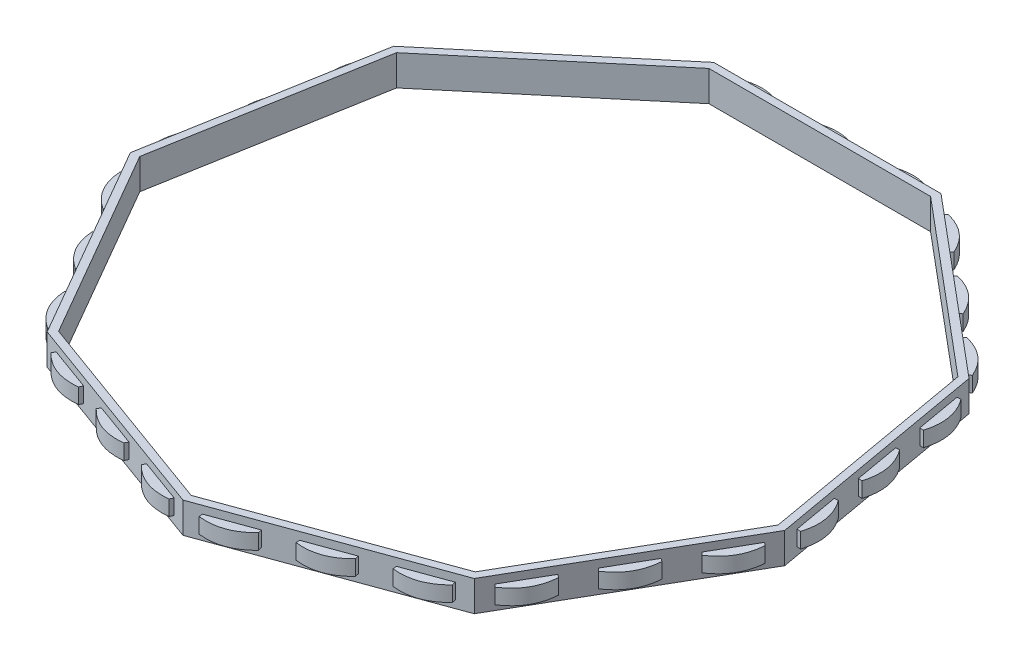
SolidWorks part; units mm, degrees
ref_plane "Front" through (0, 0, 0) normal (0, 0, 1) x (1, 0, 0)
ref_plane "Top" through (0, 0, 0) normal (0, 1, 0) x (1, 0, 0)
ref_plane "Right" through (0, 0, 0) normal (1, 0, 0) x (0, 0, -1)
sketch "Esboço1" plane through (0, 0, 0) normal (0, 1, 0) x (1, 0, 0)
  line L9 (90.0427, -15.0933) -> (79.7183, 43.4593)
  line L10 (79.7183, 43.4593) -> (34.1725, 81.6768)
  line L11 (34.1725, 81.6768) -> (-25.2834, 81.6768)
  line L12 (-25.2834, 81.6768) -> (-70.8293, 43.4593)
  line L13 (-70.8293, 43.4593) -> (-81.1537, -15.0933)
  line L14 (-81.1537, -15.0933) -> (-51.4257, -66.5836)
  line L15 (-51.4257, -66.5836) -> (4.4445, -86.9187)
  line L16 (4.4445, -86.9187) -> (60.3148, -66.5836)
  line L17 (60.3148, -66.5836) -> (90.0427, -15.0933)
  line L18 (-24.5555, 79.6768) -> (-68.986, 42.3952)
  line L19 (-68.986, 42.3952) -> (-79.0576, -14.7237)
  line L20 (-79.0576, -14.7237) -> (-50.0576, -64.9532)
  line L21 (-50.0576, -64.9532) -> (4.4445, -84.7903)
  line L22 (4.4445, -84.7903) -> (58.9467, -64.9532)
  line L23 (58.9467, -64.9532) -> (87.9467, -14.7237)
  line L24 (87.9467, -14.7237) -> (77.8751, 42.3952)
  line L25 (77.8751, 42.3952) -> (33.4445, 79.6768)
  line L26 (33.4445, 79.6768) -> (-24.5555, 79.6768)
  line L27 (-24.5555, 79.6768) -> (-68.986, 42.3952)
  line L28 (-68.986, 42.3952) -> (-79.0576, -14.7237)
  line L29 (-79.0576, -14.7237) -> (-50.0576, -64.9532)
  line L30 (-50.0576, -64.9532) -> (4.4445, -84.7903)
  line L31 (4.4445, -84.7903) -> (58.9467, -64.9532)
  line L32 (58.9467, -64.9532) -> (87.9467, -14.7237)
  line L33 (87.9467, -14.7237) -> (77.8751, 42.3952)
  line L34 (77.8751, 42.3952) -> (33.4445, 79.6768)
  line L35 (33.4445, 79.6768) -> (-24.5555, 79.6768)
  dimension "D1" = 0
  dimension "D2" = 2
extrude "Ressalto-extrusão1" add sketch "Esboço1" along normal mid plane 8
sketch "Esboço3" plane through (0, 0, 0) normal (0, 1, 0) x (1, 0, 0)
  line L0 (19.4796, -81.4464) -> (8.2033, -85.5506)
  line L1 (8.2033, -85.5506) -> (8.2988, -86.546)
  line L2 (4.4445, -86.9187) -> (60.3148, -66.5836) construction
  line L3 (19.7122, -82.4189) -> (19.4796, -81.4464)
  line L4 (38.0762, -74.6778) -> (26.7998, -78.782)
  line L5 (19.7122, -82.4189) -> (15.0322, -87.3218) construction
  line L6 (15.0322, -87.3218) -> (8.2988, -86.546) construction
  line L7 (26.7998, -78.782) -> (26.8953, -79.7775)
  line L8 (38.3088, -75.6503) -> (38.0762, -74.6778)
  line L9 (38.3088, -75.6503) -> (33.6287, -80.5532) construction
  line L10 (33.6287, -80.5532) -> (26.8953, -79.7775) construction
  line L11 (56.6727, -67.9092) -> (45.3964, -72.0134)
  line L12 (45.3964, -72.0134) -> (45.4918, -73.0089)
  line L13 (56.9053, -68.8818) -> (56.6727, -67.9092)
  line L14 (56.9053, -68.8818) -> (52.2253, -73.7846) construction
  line L15 (52.2253, -73.7846) -> (45.4918, -73.0089) construction
  line L16 (-36.3906, -72.0559) -> (-47.6669, -67.9517)
  line L17 (-47.6669, -67.9517) -> (-48.2337, -68.7756)
  line L18 (-36.8376, -72.9504) -> (-36.3906, -72.0559)
  line L19 (-17.7941, -78.8245) -> (-29.0704, -74.7202)
  line L20 (-29.0704, -74.7202) -> (-29.6371, -75.5441)
  line L21 (-18.2411, -79.719) -> (-17.7941, -78.8245)
  line L22 (0.8024, -85.5931) -> (-10.4739, -81.4888)
  line L23 (-10.4739, -81.4888) -> (-11.0406, -82.3127)
  line L24 (0.3555, -86.4876) -> (0.8024, -85.5931)
  line L25 (-36.8376, -72.9504) -> (-43.5742, -73.698) construction
  line L26 (-43.5742, -73.698) -> (-48.2337, -68.7756) construction
  line L27 (-18.2411, -79.719) -> (-24.9777, -80.4666) construction
  line L28 (-24.9777, -80.4666) -> (-29.6371, -75.5441) construction
  line L29 (0.3555, -86.4876) -> (-6.3812, -87.2352) construction
  line L31 (-6.3812, -87.2352) -> (-11.0406, -82.3127) construction
  line L32 (-73.1537, -28.9497) -> (-79.1537, -18.5574)
  line L33 (-79.1537, -18.5574) -> (-80.1174, -18.8242)
  line L34 (-74.0711, -29.3476) -> (-73.1537, -28.9497)
  line L35 (-63.2586, -46.0883) -> (-69.2586, -35.696)
  line L36 (-69.2586, -35.696) -> (-70.2224, -35.9629)
  line L37 (-64.176, -46.4863) -> (-63.2586, -46.0883)
  line L38 (-53.3636, -63.227) -> (-59.3636, -52.8347)
  line L39 (-59.3636, -52.8347) -> (-60.3274, -53.1015)
  line L40 (-54.281, -63.625) -> (-53.3636, -63.227)
  line L41 (-74.0711, -29.3476) -> (-79.7121, -25.5901) construction
  line L42 (-79.7121, -25.5901) -> (-80.1174, -18.8242) construction
  line L43 (-64.176, -46.4863) -> (-69.8171, -42.7287) construction
  line L44 (-69.8171, -42.7287) -> (-70.2224, -35.9629) construction
  line L45 (-54.281, -63.625) -> (-59.9221, -59.8674) construction
  line L46 (-59.9221, -59.8674) -> (-60.3274, -53.1015) construction
  line L47 (-73.6076, 27.7024) -> (-71.5238, 39.5201)
  line L48 (-71.5238, 39.5201) -> (-72.4336, 39.9352)
  line L49 (-74.5662, 27.9873) -> (-73.6076, 27.7024)
  line L50 (-77.0441, 8.2131) -> (-74.9603, 20.0307)
  line L51 (-74.9603, 20.0307) -> (-75.8701, 20.4458)
  line L52 (-78.0027, 8.4979) -> (-77.0441, 8.2131)
  line L53 (-80.4806, -11.2763) -> (-78.3968, 0.5414)
  line L54 (-78.3968, 0.5414) -> (-79.3066, 0.9564)
  line L55 (-81.4392, -10.9915) -> (-80.4806, -11.2763)
  line L56 (-74.5662, 27.9873) -> (-76.4722, 34.4917) construction
  line L57 (-76.4722, 34.4917) -> (-72.4336, 39.9352) construction
  line L58 (-78.0027, 8.4979) -> (-79.9087, 15.0024) construction
  line L59 (-79.9087, 15.0024) -> (-75.8701, 20.4458) construction
  line L60 (-81.4392, -10.9915) -> (-83.3452, -4.487) construction
  line L63 (-83.3452, -4.487) -> (-79.3066, 0.9564) construction
  line L64 (-37.5401, 71.3922) -> (-28.3476, 79.1057)
  line L65 (-28.3476, 79.1057) -> (-28.7777, 80.0085)
  line L66 (-38.0913, 72.2266) -> (-37.5401, 71.3922)
  line L67 (-52.7001, 58.6715) -> (-43.5076, 66.3849)
  line L68 (-43.5076, 66.3849) -> (-43.9378, 67.2877)
  line L69 (-53.2514, 59.5058) -> (-52.7001, 58.6715)
  line L70 (-67.8602, 45.9507) -> (-58.6676, 53.6641)
  line L71 (-58.6676, 53.6641) -> (-59.0978, 54.5669)
  line L72 (-68.4114, 46.785) -> (-67.8602, 45.9507)
  line L73 (-38.0913, 72.2266) -> (-35.3704, 78.4345) construction
  line L74 (-35.3704, 78.4345) -> (-28.7777, 80.0085) construction
  line L75 (-53.2514, 59.5058) -> (-50.5305, 65.7137) construction
  line L76 (-50.5305, 65.7137) -> (-43.9378, 67.2877) construction
  line L77 (-68.4114, 46.785) -> (-65.6905, 52.9929) construction
  line L78 (-65.6905, 52.9929) -> (-59.0978, 54.5669) construction
  line L79 (18.1725, 81.6768) -> (30.1725, 81.6768)
  line L80 (30.1725, 81.6768) -> (30.4232, 82.6449)
  line L81 (18.2865, 82.6703) -> (18.1725, 81.6768)
  line L82 (-1.6175, 81.6768) -> (10.3825, 81.6768)
  line L83 (10.3825, 81.6768) -> (10.6332, 82.6449)
  line L84 (-1.5035, 82.6703) -> (-1.6175, 81.6768)
  line L85 (-21.4076, 81.6768) -> (-9.4076, 81.6768)
  line L86 (-9.4076, 81.6768) -> (-9.1568, 82.6449)
  line L87 (-21.2935, 82.6703) -> (-21.4076, 81.6768)
  line L88 (18.2865, 82.6703) -> (24.3612, 85.6768) construction
  line L89 (24.3612, 85.6768) -> (30.4232, 82.6449) construction
  line L90 (-1.5035, 82.6703) -> (4.5712, 85.6768) construction
  line L91 (4.5712, 85.6768) -> (10.6332, 82.6449) construction
  line L92 (-21.2935, 82.6703) -> (-15.2188, 85.6768) construction
  line L93 (-15.2188, 85.6768) -> (-9.1568, 82.6449) construction
  line L94 (67.4616, 53.7439) -> (76.6541, 46.0305)
  line L95 (76.6541, 46.0305) -> (77.4685, 46.6109)
  line L96 (68.1876, 54.4317) -> (67.4616, 53.7439)
  line L97 (52.3016, 66.4647) -> (61.4941, 58.7513)
  line L98 (61.4941, 58.7513) -> (62.3085, 59.3316)
  line L99 (53.0275, 67.1525) -> (52.3016, 66.4647)
  line L100 (37.1415, 79.1855) -> (46.3341, 71.472)
  line L101 (46.3341, 71.472) -> (47.1484, 72.0524)
  line L102 (37.8675, 79.8732) -> (37.1415, 79.1855)
  line L103 (68.1876, 54.4317) -> (74.7736, 52.8301) construction
  line L104 (74.7736, 52.8301) -> (77.4685, 46.6109) construction
  line L105 (53.0275, 67.1525) -> (59.6136, 65.5509) construction
  line L106 (59.6136, 65.5509) -> (62.3085, 59.3316) construction
  line L107 (37.8675, 79.8732) -> (44.4535, 78.2716) construction
  line L108 (44.4535, 78.2716) -> (47.1484, 72.0524) construction
  line L109 (87.2644, 0.6637) -> (89.3481, -11.154)
  line L110 (89.3481, -11.154) -> (90.345, -11.2329)
  line L111 (88.2625, 0.7238) -> (87.2644, 0.6637)
  line L112 (83.8279, 20.153) -> (85.9116, 8.3353)
  line L113 (85.9116, 8.3353) -> (86.9085, 8.2565)
  line L114 (84.826, 20.2132) -> (83.8279, 20.153)
  line L115 (80.3914, 39.6424) -> (82.4751, 27.8247)
  line L116 (82.4751, 27.8247) -> (83.472, 27.7458)
  line L117 (81.3895, 39.7026) -> (80.3914, 39.6424)
  line L118 (88.2625, 0.7238) -> (92.2783, -4.7365) construction
  line L119 (92.2783, -4.7365) -> (90.345, -11.2329) construction
  line L120 (84.826, 20.2132) -> (88.8418, 14.7529) construction
  line L121 (88.8418, 14.7529) -> (86.9085, 8.2565) construction
  line L122 (81.3895, 39.7026) -> (85.4053, 34.2423) construction
  line L123 (85.4053, 34.2423) -> (83.472, 27.7458) construction
  line L124 (68.3148, -52.7272) -> (62.3148, -63.1195)
  line L125 (62.3148, -63.1195) -> (63.0278, -63.8207)
  line L126 (69.1181, -53.3227) -> (68.3148, -52.7272)
  line L127 (78.2098, -35.5885) -> (72.2098, -45.9808)
  line L128 (72.2098, -45.9808) -> (72.9228, -46.682)
  line L129 (79.0131, -36.184) -> (78.2098, -35.5885)
  line L130 (88.1048, -18.4499) -> (82.1048, -28.8422)
  line L131 (82.1048, -28.8422) -> (82.8178, -29.5433)
  line L132 (88.9082, -19.0454) -> (88.1048, -18.4499)
  line L133 (69.1181, -53.3227) -> (68.6845, -60.0868) construction
  line L134 (68.6845, -60.0868) -> (63.0278, -63.8207) construction
  line L135 (79.0131, -36.184) -> (78.5795, -42.9481) construction
  line L136 (78.5795, -42.9481) -> (72.9228, -46.682) construction
  line L137 (88.9082, -19.0454) -> (88.4745, -25.8095) construction
  line L138 (88.4745, -25.8095) -> (82.8178, -29.5433) construction
  spline S0 degree 2 poles (19.7122, -82.4189) (15.0322, -87.3218) (8.2988, -86.546) knots 0 0 0 1 1 1
  spline S1 degree 2 poles (38.3088, -75.6503) (33.6287, -80.5532) (26.8953, -79.7775) knots 0 0 0 1 1 1
  spline S2 degree 2 poles (56.9053, -68.8818) (52.2253, -73.7846) (45.4918, -73.0089) knots 0 0 0 1 1 1
  spline S3 degree 2 poles (-36.8376, -72.9504) (-43.5742, -73.698) (-48.2337, -68.7756) knots 0 0 0 1 1 1
  spline S4 degree 2 poles (-18.2411, -79.719) (-24.9777, -80.4666) (-29.6371, -75.5441) knots 0 0 0 1 1 1
  spline S5 degree 2 poles (0.3555, -86.4876) (-6.3812, -87.2352) (-11.0406, -82.3127) knots 0 0 0 1 1 1
  spline S6 degree 2 poles (-74.0711, -29.3476) (-79.7121, -25.5901) (-80.1174, -18.8242) knots 0 0 0 1 1 1
  spline S7 degree 2 poles (-64.176, -46.4863) (-69.8171, -42.7287) (-70.2224, -35.9629) knots 0 0 0 1 1 1
  spline S8 degree 2 poles (-54.281, -63.625) (-59.9221, -59.8674) (-60.3274, -53.1015) knots 0 0 0 1 1 1
  spline S9 degree 2 poles (-74.5662, 27.9873) (-76.4722, 34.4917) (-72.4336, 39.9352) knots 0 0 0 1 1 1
  spline S10 degree 2 poles (-78.0027, 8.4979) (-79.9087, 15.0024) (-75.8701, 20.4458) knots 0 0 0 1 1 1
  spline S11 degree 2 poles (-81.4392, -10.9915) (-83.3452, -4.487) (-79.3066, 0.9564) knots 0 0 0 1 1 1
  spline S12 degree 2 poles (-38.0913, 72.2266) (-35.3704, 78.4345) (-28.7777, 80.0085) knots 0 0 0 1 1 1
  spline S13 degree 2 poles (-53.2514, 59.5058) (-50.5305, 65.7137) (-43.9378, 67.2877) knots 0 0 0 1 1 1
  spline S14 degree 2 poles (-68.4114, 46.785) (-65.6905, 52.9929) (-59.0978, 54.5669) knots 0 0 0 1 1 1
  spline S15 degree 2 poles (18.2865, 82.6703) (24.3612, 85.6768) (30.4232, 82.6449) knots 0 0 0 1 1 1
  spline S16 degree 2 poles (-1.5035, 82.6703) (4.5712, 85.6768) (10.6332, 82.6449) knots 0 0 0 1 1 1
  spline S17 degree 2 poles (-21.2935, 82.6703) (-15.2188, 85.6768) (-9.1568, 82.6449) knots 0 0 0 1 1 1
  spline S18 degree 2 poles (68.1876, 54.4317) (74.7736, 52.8301) (77.4685, 46.6109) knots 0 0 0 1 1 1
  spline S19 degree 2 poles (53.0275, 67.1525) (59.6136, 65.5509) (62.3085, 59.3316) knots 0 0 0 1 1 1
  spline S20 degree 2 poles (37.8675, 79.8732) (44.4535, 78.2716) (47.1484, 72.0524) knots 0 0 0 1 1 1
  spline S21 degree 2 poles (88.2625, 0.7238) (92.2783, -4.7365) (90.345, -11.2329) knots 0 0 0 1 1 1
  spline S22 degree 2 poles (84.826, 20.2132) (88.8418, 14.7529) (86.9085, 8.2565) knots 0 0 0 1 1 1
  spline S23 degree 2 poles (81.3895, 39.7026) (85.4053, 34.2423) (83.472, 27.7458) knots 0 0 0 1 1 1
  spline S24 degree 2 poles (69.1181, -53.3227) (68.6845, -60.0868) (63.0278, -63.8207) knots 0 0 0 1 1 1
  spline S25 degree 2 poles (79.0131, -36.184) (78.5795, -42.9481) (72.9228, -46.682) knots 0 0 0 1 1 1
  spline S26 degree 2 poles (88.9082, -19.0454) (88.4745, -25.8095) (82.8178, -29.5433) knots 0 0 0 1 1 1
  point P2 (0, 0)
  point P8 (0, 0)
  point P11 (5.8289, 0)
  point P16 (79.7993, 32.1228)
  point P28 (4.4445, 0)
  point P144 (4.4445, 0)
  point P145 (5.8289, -6.3337)
  point P146 (0, 0)
  dimension "D1" = 1
  dimension "D2" = 4
  dimension "D3" = 12
  dimension "D4" = 3
  dimension "D5" = 4
extrude "Ressalto-extrusão2" add sketch "Esboço3" along normal mid plane 4
